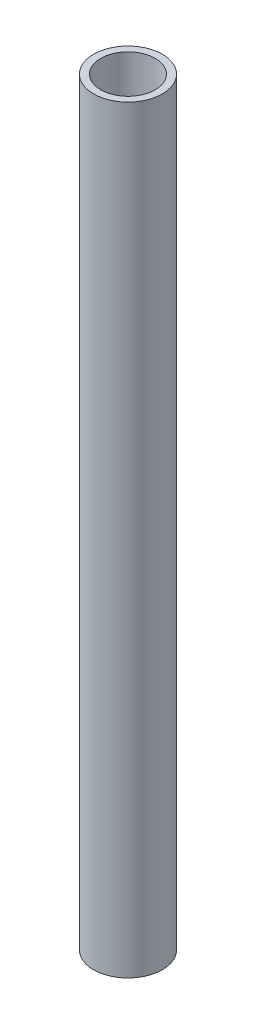
SolidWorks part; units mm, degrees
material "Thornel Mat VMA"
ref_plane "Front Plane" through (0, 0, 0) normal (0, 0, 1) x (1, 0, 0)
ref_plane "Top Plane" through (0, 0, 0) normal (0, 1, 0) x (1, 0, 0)
ref_plane "Right Plane" through (0, 0, 0) normal (1, 0, 0) x (0, 0, -1)
sketch "Sketch1" plane through (0, 0, 0) normal (0, 1, 0) x (1, 0, 0)
  circle A0 centre (0, 0) radius 14.5
  dimension "D1" = 29
extrude "Boss-Extrude1" add sketch "Sketch1" along normal blind 320
shell "Shell1" thickness 3
